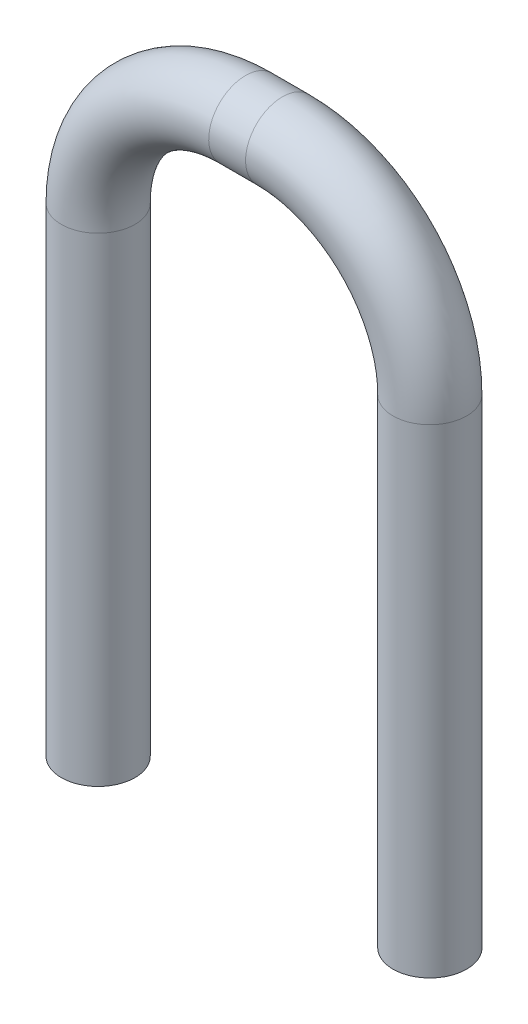
SolidWorks part; units mm, degrees
ref_plane "Front" through (0, 0, 0) normal (0, 0, 1) x (1, 0, 0)
ref_plane "Top" through (0, 0, 0) normal (0, 1, 0) x (1, 0, 0)
ref_plane "Right" through (0, 0, 0) normal (1, 0, 0) x (0, 0, -1)
sketch "Esquisse1" plane through (0, 0, 0) normal (0, 0, 1) x (1, 0, 0)
  line L1 (-0.5, 17) -> (0.5, 17)
  line L2 (-4.5, 13) -> (-4.5, 0)
  line L3 (-4.5, 0) -> (4.5, 0) construction
  line L4 (4.5, 13) -> (4.5, 0)
  arc A0 (0.5, 17) -> (4.5, 13) centre (0.5, 13) cw
  arc A1 (-0.5, 17) -> (-4.5, 13) centre (-0.5, 13) ccw
  dimension "D1" = 4
  dimension "D2" = 17
  dimension "D3" = 9
sweep "Balayage1" add path "Esquisse1" circular profile diameter 2 parameters "D3"=2
